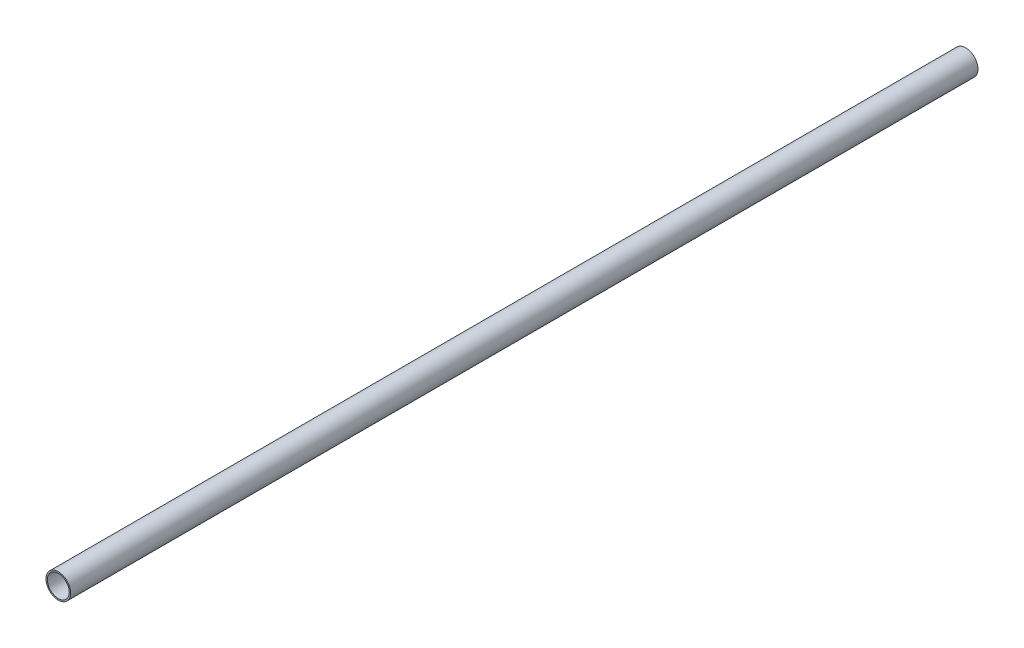
SolidWorks part; units mm, degrees
material "AISI 4130 Steel, annealed at 865C"
ref_plane "Front Plane" through (0, 0, 0) normal (0, 0, 1) x (1, 0, 0)
ref_plane "Top Plane" through (0, 0, 0) normal (0, 1, 0) x (1, 0, 0)
ref_plane "Right Plane" through (0, 0, 0) normal (1, 0, 0) x (0, 0, -1)
sketch "Sketch1" plane through (0, 0, 0) normal (0, 0, 1) x (1, 0, 0)
  circle A0 centre (0, 0) radius 7.0485
  circle A1 centre (0, 0) radius 7.9375
  dimension "D1" = 15.875
  dimension "D2" = 0.889
extrude "Boss-Extrude1" add sketch "Sketch1" along normal mid plane 584.2
equation "\"Torsion Bar Length\"= 23in"
equation "\"D1@Boss-Extrude1\"=\"Torsion Bar Length\""
